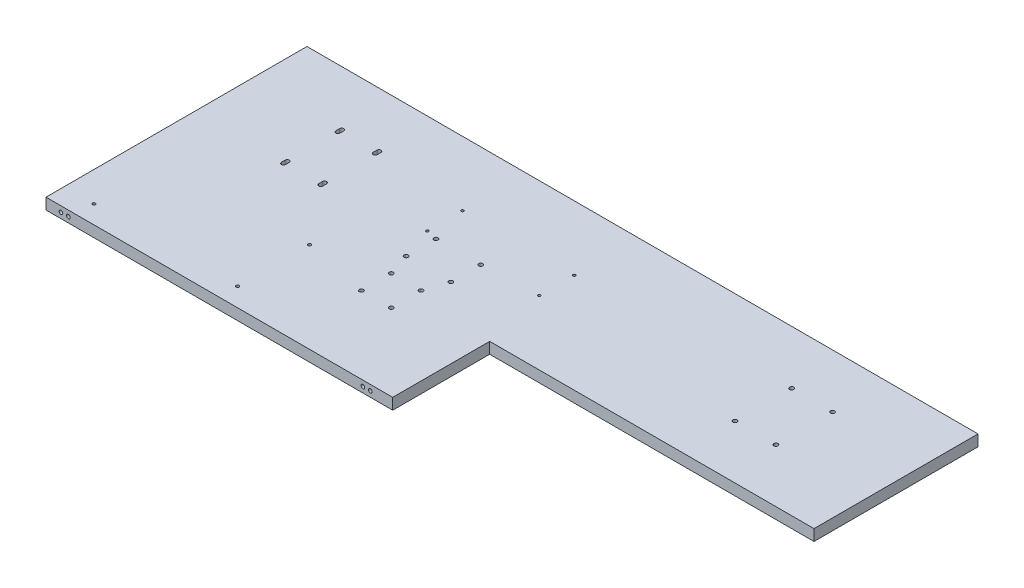
SolidWorks part; units mm, degrees
ref_plane "Front Plane" through (0, 0, 0) normal (0, 0, 1) x (1, 0, 0)
ref_plane "Top Plane" through (0, 0, 0) normal (0, 1, 0) x (1, 0, 0)
ref_plane "Right Plane" through (0, 0, 0) normal (1, 0, 0) x (0, 0, -1)
sketch "Sketch1" plane through (0, 0, 0) normal (0, 1, 0) x (1, 0, 0)
  line L1 (-450, 175) -> (450, 175)
  line L2 (-450, 175) -> (-450, -175)
  line L3 (-450, -175) -> (450, -175)
  line L4 (450, 175) -> (450, -175)
  line L5 (-450, 175) -> (450, -175) construction
  line L6 (-450, -175) -> (450, 175) construction
  point P0 (0, 0)
  dimension "D1" = 900
  dimension "D2" = 350
extrude "Boss-Extrude1" add sketch "Sketch1" along normal blind 15
sketch "Sketch2" plane through (0, 15, 0) normal (0, 1, 0) x (1, 0, 0)
  line L0 (-280, 23.5) -> (-280, 28.5) construction
  line L1 (-282.75, 23.5) -> (-282.75, 28.5)
  line L2 (-330, 101.5) -> (-330, 96.5) construction
  line L3 (-327.25, 101.5) -> (-327.25, 96.5)
  line L4 (-332.75, 101.5) -> (-332.75, 96.5)
  line L5 (-330, 28.5) -> (-330, 23.5) construction
  line L6 (-327.25, 28.5) -> (-327.25, 23.5)
  line L7 (-332.75, 28.5) -> (-332.75, 23.5)
  line L8 (-450, 175) -> (-450, -175) construction
  line L9 (450, 175) -> (-450, 175) construction
  line L10 (-277.25, 23.5) -> (-277.25, 28.5)
  line L11 (-280, 96.5) -> (-280, 101.5) construction
  line L12 (-282.75, 96.5) -> (-282.75, 101.5)
  line L13 (-277.25, 96.5) -> (-277.25, 101.5)
  arc A4 (-327.25, 101.5) -> (-332.75, 101.5) centre (-330, 101.5) ccw
  arc A5 (-332.75, 96.5) -> (-327.25, 96.5) centre (-330, 96.5) ccw
  arc A6 (-327.25, 28.5) -> (-332.75, 28.5) centre (-330, 28.5) ccw
  arc A7 (-332.75, 23.5) -> (-327.25, 23.5) centre (-330, 23.5) ccw
  arc A8 (-282.75, 23.5) -> (-277.25, 23.5) centre (-280, 23.5) ccw
  arc A9 (-277.25, 28.5) -> (-282.75, 28.5) centre (-280, 28.5) ccw
  arc A10 (-282.75, 96.5) -> (-277.25, 96.5) centre (-280, 96.5) ccw
  arc A11 (-277.25, 101.5) -> (-282.75, 101.5) centre (-280, 101.5) ccw
  point P2 (-280, 26)
  point P8 (-330, 99)
  point P18 (-330, 26)
  point P25 (-280, 99)
  dimension "D1" = 73
  dimension "D4" = 120
  dimension "D3" = 2.75
  dimension "D2" = 5
  dimension "D5" = 76
  dimension "D6" = 50
extrude "Cut-Extrude1" cut sketch "Sketch2" against normal up to next
sketch "Sketch3" plane through (0, 15, 0) normal (0, 1, 0) x (1, 0, 0)
  line L0 (-450, -175) -> (450, -175) construction
  line L1 (-450, 175) -> (-450, -175) construction
  circle A0 centre (-218.0015, -53.5) radius 2
  circle A1 centre (-218.0015, -150) radius 2
  circle A3 centre (-410, -150.75) radius 2
  dimension "D1" = 4
  dimension "D2" = 96.5
  dimension "D3" = 192
  dimension "D4" = 25
  dimension "D5" = 40
  dimension "D6" = 0.75
extrude "Cut-Extrude2" cut sketch "Sketch3" against normal up to next
sketch "Sketch10" plane through (0, 15, 0) normal (0, 1, 0) x (1, 0, 0)
  circle A8 centre (-140, 38) radius 2.75
  circle A9 centre (-140, -2) radius 2.75
  circle A10 centre (-80, -2) radius 2.75
  circle A11 centre (-80, 38) radius 2.75
  circle A12 centre (-130, -32) radius 2.75
  circle A13 centre (-90, -32) radius 2.75
  circle A14 centre (-130, -72) radius 2.75
  circle A15 centre (-90, -72) radius 2.75
  dimension "D2" = 5.5
  dimension "D7" = 10
  dimension "D1" = 12
  dimension "D3" = 40
  dimension "D4" = 190
  dimension "D5" = 60
  dimension "D6" = 30
  dimension "D8" = 40
  dimension "D9" = 40
extrude "Cut-Extrude6" cut sketch "Sketch10" against normal through all
sketch "Sketch11" plane through (0, 15, 0) normal (0, 1, 0) x (1, 0, 0)
  circle A0 centre (-155, 88.5) radius 1.75
  circle A1 centre (-155, 41.5) radius 1.75
  circle A2 centre (-5, 88.5) radius 1.75
  circle A3 centre (-5, 41.5) radius 1.75
  dimension "D4" = 3.5
  dimension "D1" = 175
  dimension "D2" = 15.5
  dimension "D3" = 150
  dimension "D5" = 47
extrude "Cut-Extrude7" cut sketch "Sketch11" against normal through all
sketch "Sketch12" plane through (0, 15, 0) normal (0, 1, 0) x (1, 0, 0)
  circle A0 centre (272, 103) radius 2.75
  circle A1 centre (327, 103) radius 2.75
  circle A2 centre (272, 27) radius 2.75
  circle A3 centre (327, 27) radius 2.75
  dimension "D3" = 5.5
  dimension "D1" = 76
  dimension "D2" = 55
  dimension "D4" = 1
  dimension "D5" = 602
extrude "Cut-Extrude8" cut sketch "Sketch12" against normal through all
sketch "Sketch13" plane through (0, 0, -175) normal (0, 0, -1) x (-1, 0, 0)
  circle A0 centre (15, 7.5) radius 2.5
  circle A1 centre (25, 7.5) radius 2.5
  circle A2 centre (430, 7.5) radius 2.5
  circle A3 centre (420, 7.5) radius 2.5
extrude "Cut-Extrude9" cut sketch "Sketch13" against normal blind 10
mirror "Mirror1" about plane through (0, 0, 0) normal (0, 0, 1) of "Cut-Extrude9"
sketch "Sketch14" plane through (-450, 0, 0) normal (-1, 0, 0) x (0, 0, 1)
  circle A0 centre (-145, 7.5) radius 2.5
  circle A1 centre (-135, 7.5) radius 2.5
  circle A2 centre (145, 7.5) radius 2.5
  circle A3 centre (135, 7.5) radius 2.5
extrude "Cut-Extrude10" cut sketch "Sketch14" against normal blind 10
sketch "Sketch15" plane through (0, 15, 0) normal (0, 1, 0) x (1, 0, 0)
  line L0 (-450, -175) -> (450, -175) construction
  line L1 (15.0209, -175) -> (450, -175)
  line L2 (15.0209, -175) -> (15.0209, -44.9634)
  line L3 (15.0209, -44.9634) -> (450, -44.9634)
  line L4 (450, -175) -> (450, -44.9634)
  line L5 (450, -175) -> (450, 175) construction
extrude "Cut-Extrude11" cut sketch "Sketch15" against normal through all
